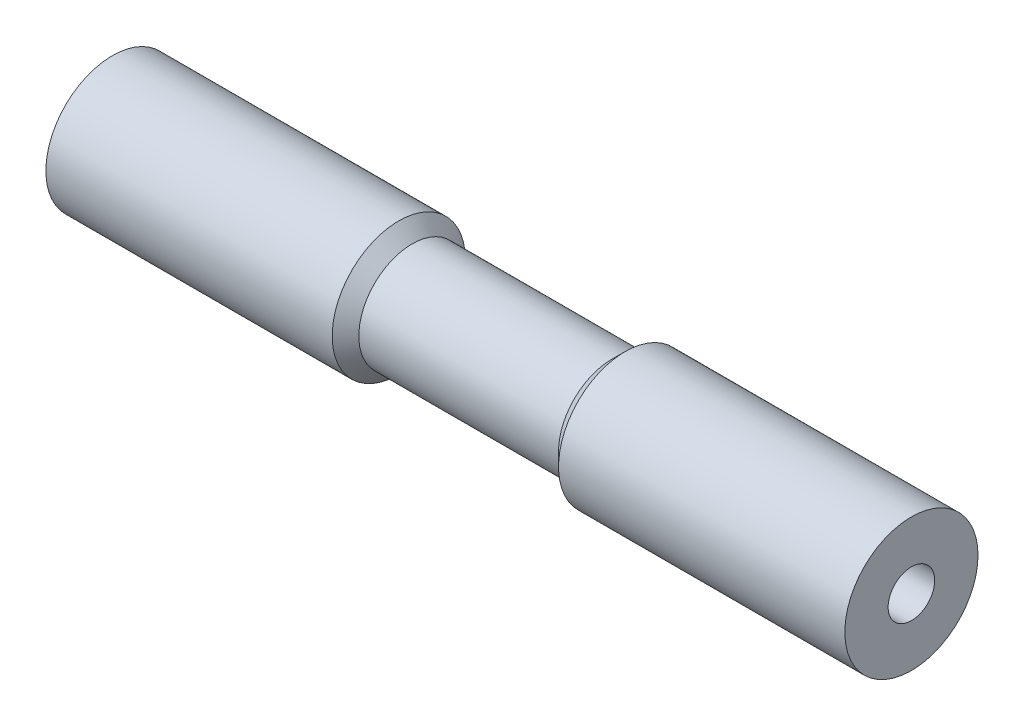
SolidWorks part; units mm, degrees
ref_plane "Front Plane" through (0, 0, 0) normal (0, 0, 1) x (1, 0, 0)
ref_plane "Top Plane" through (0, 0, 0) normal (0, 1, 0) x (1, 0, 0)
ref_plane "Right Plane" through (0, 0, 0) normal (1, 0, 0) x (0, 0, -1)
sketch "Sketch2" plane through (0, 0, 0) normal (0, 0, 1) x (1, 0, 0)
  line L0 (0, 0) -> (0, 10)
  line L1 (0, 10) -> (43, 10)
  line L2 (43, 10) -> (45, 8)
  line L3 (45, 8) -> (75, 8)
  line L4 (75, 8) -> (77, 10)
  line L5 (77, 10) -> (120, 10)
  line L7 (120, 0) -> (0, 0)
  line L8 (60, 0) -> (60, 8) construction
  line L9 (120, 10) -> (120, 4)
  line L10 (120, 0) -> (120, 4)
  point P3 (60, 8)
  dimension "D1" = 45
  dimension "D2" = 45
  dimension "D3" = 10
  dimension "D4" = 120
  dimension "D5" = 8
  dimension "D6" = 30
  dimension "D8" = 4
revolve "Revolve1" add sketch "Sketch2" angle 360 about L7
sketch "Sketch3" plane through (0, 0, 0) normal (-1, 0, 0) x (0, 0, 1)
  line L0 (-1.118, 1) -> (1.118, 1) construction
  line L1 (-1.1832, 1.15) -> (1.1832, 1.15)
  arc A0 (-1.118, 1) -> (1.118, 1) centre (0, 0) ccw construction
  arc A1 (-1.1832, 1.15) -> (1.1832, 1.15) centre (0, 0) ccw
  point P5 (0, -1.5)
  dimension "D1" = 3
  dimension "D2" = 2.5
  dimension "D3" = 0.15
extrude "Cut-Extrude1" cut sketch "Sketch3" against normal blind 20
sketch "Sketch5" plane through (120, 0, 0) normal (1, 0, 0) x (0, 0, -1)
  circle A0 centre (0, 0) radius 3.5
  dimension "D1" = 7
extrude "Cut-Extrude2" cut sketch "Sketch5" against normal blind 50
